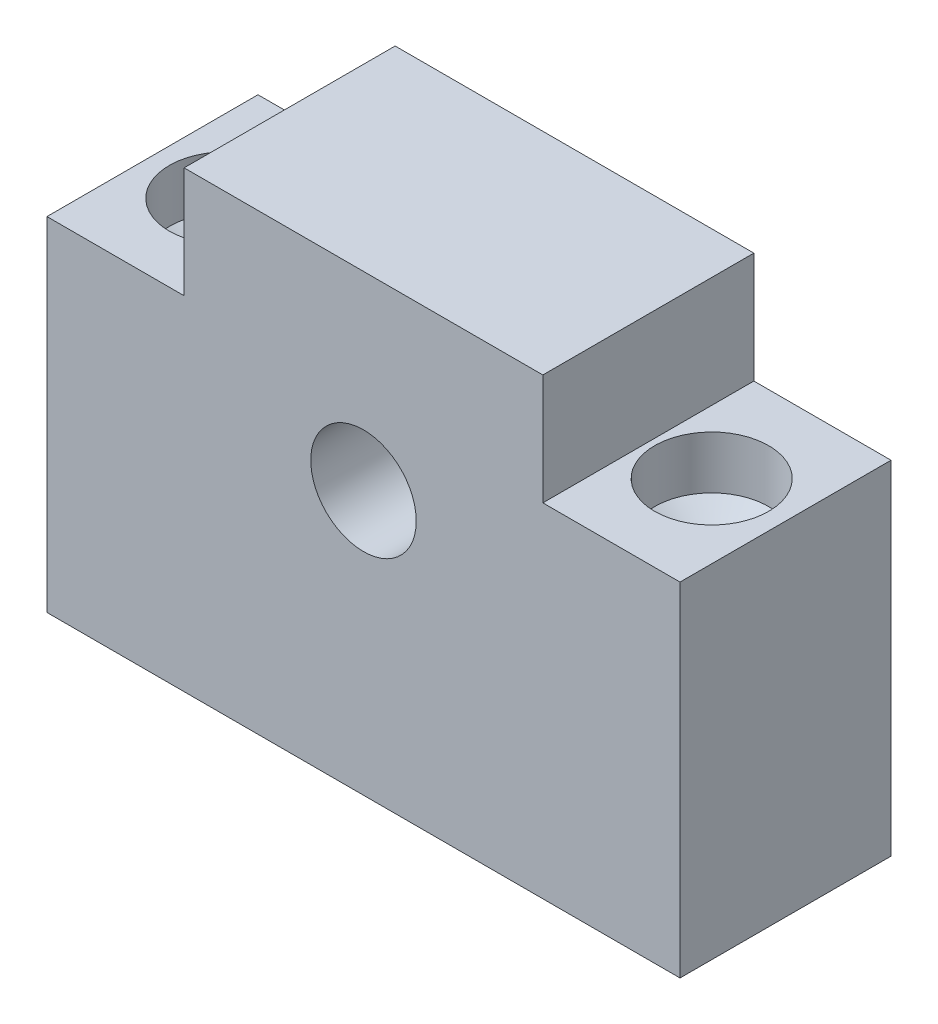
SolidWorks part; units mm, degrees
ref_plane "Front Plane" through (0, 0, 0) normal (0, 0, 1) x (1, 0, 0)
ref_plane "Top Plane" through (0, 0, 0) normal (0, 1, 0) x (1, 0, 0)
ref_plane "Right Plane" through (0, 0, 0) normal (1, 0, 0) x (0, 0, -1)
sketch "Sketch1" plane through (0, 0, 0) normal (0, 0, 1) x (1, 0, 0)
  line L0 (-17, 16.25) -> (-17, 26.75)
  line L1 (-30, 16.25) -> (-17, 16.25)
  line L2 (-30, 16.25) -> (-30, -16.25)
  line L3 (-30, -16.25) -> (30, -16.25)
  line L4 (30, 16.25) -> (30, -16.25)
  line L5 (-30, 16.25) -> (30, -16.25) construction
  line L6 (-30, -16.25) -> (30, 16.25) construction
  line L7 (-17, 26.75) -> (17, 26.75)
  line L8 (17, 26.75) -> (17, 16.25)
  line L9 (17, 16.25) -> (30, 16.25)
  point P0 (0, 0)
  dimension "D1" = 60
  dimension "D2" = 32.5
  dimension "D3" = 43
  dimension "D4" = 34
  dimension "D5" = 13
extrude "Boss-Extrude1" add sketch "Sketch1" along normal blind 20
sketch "Sketch2" plane through (0, 0, 20) normal (0, 0, 1) x (1, 0, 0)
  line L0 (-30, -16.25) -> (30, -16.25) construction
  line L1 (30, -16.25) -> (30, 16.25) construction
  circle A0 centre (0, 8.75) radius 5
  dimension "D3" = 10
  dimension "D1" = 25
  dimension "D2" = 30
extrude "Cut-Extrude1" cut sketch "Sketch2" against normal blind 10
sketch "Sketch3" plane through (0, 0, 0) normal (0, 0, -1) x (-1, 0, 0)
  line L0 (30, 16.25) -> (30, -16.25) construction
  line L1 (30, -16.25) -> (-30, -16.25) construction
  circle A0 centre (0, 8.75) radius 10
  dimension "D1" = 20
  dimension "D2" = 30
  dimension "D3" = 25
extrude "Cut-Extrude2" cut sketch "Sketch3" against normal blind 10
hole_wizard "Ø10.8 (10.8) Diameter Hole1" positions "Sketch5" profile "Sketch4" hole size "Ø10.8" standard "ISO"
sketch "Sketch5" plane through (0, 16.25, 0) normal (0, 1, 0) x (1, 0, 0)
  line L0 (-17, 0) -> (-30, 0) construction
  line L1 (30, 0) -> (17, 0) construction
  point P0 (-23, -10)
  point P2 (23, -10)
  dimension "D1" = 46
  dimension "D2" = 23
  dimension "D3" = 10
  dimension "D4" = 10
sketch "Sketch4" plane through (-23, 16.25, 10) normal (1, 0, 0) x (0, 0, 1)
  line L0 (0, 0) -> (0, 8.2446)
  line L1 (0, 8.2446) -> (5.4, 5)
  line L2 (5.4, 5) -> (5.4, 0)
  line L5 (5.4, 0) -> (0, 0)
  line L10 (0, 8.2446) -> (-5.4, 5) construction
  line L11 (0, -6.35) -> (0, 107.95) construction
  dimension "Hole Dia." = 10.8
  dimension "Hole Depth" = 5
  dimension "Drill Angle" = 118
hole_wizard "Ø6.6 (6.6) Diameter Hole1" positions "Sketch7" profile "Sketch8" hole size "Ø6.6" standard "ISO" end condition through all
sketch "Sketch7" plane through (0, 16.25, 0) normal (0, 1, 0) x (1, 0, 0)
  point P0 (-23, -10)
  point P3 (23, -10)
sketch "Sketch8" plane through (-23, 16.25, 10) normal (1, 0, 0) x (0, 0, 1)
  line L0 (0, 0) -> (0, 32.5)
  line L1 (0, 32.5) -> (3.3, 32.5)
  line L2 (3.3, 32.5) -> (3.3, 0)
  line L5 (3.3, 0) -> (0, 0)
  line L11 (0, -6.35) -> (0, 107.95) construction
  dimension "Thru Hole Dia." = 6.6
  dimension "Thru Hole Depth" = 32.5
